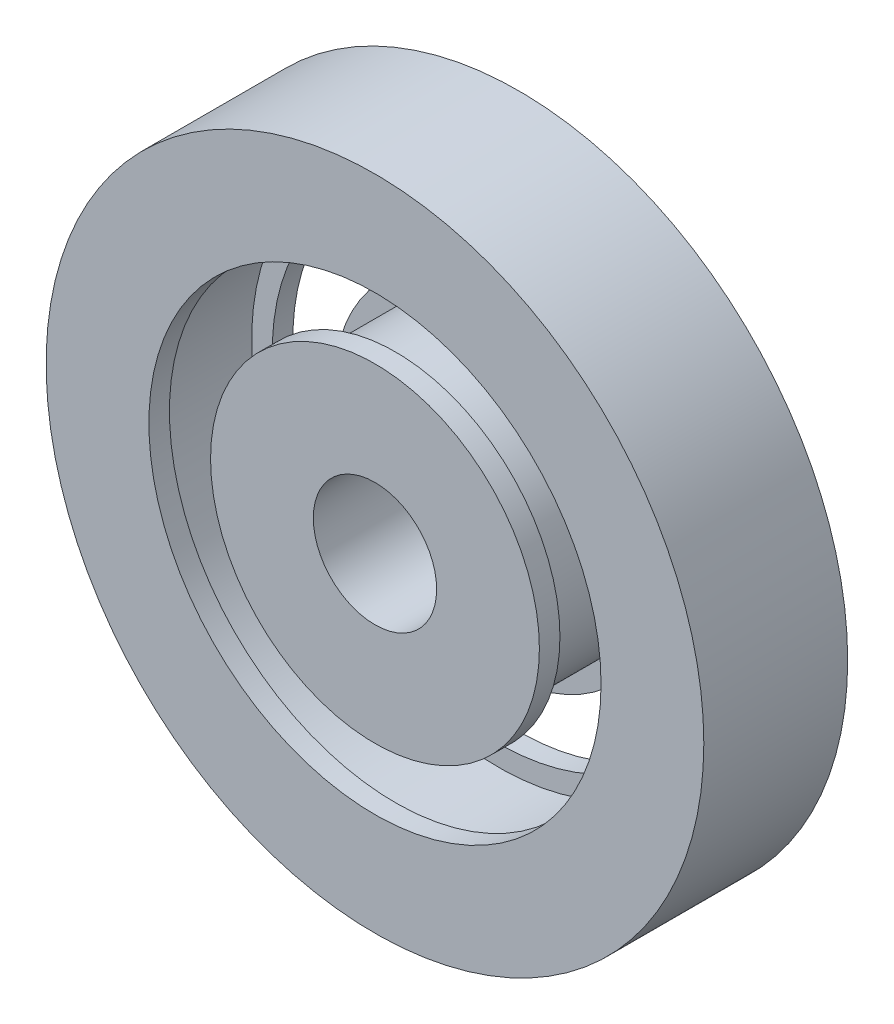
SolidWorks part; units mm, degrees
ref_plane "Front Plane" through (0, 0, 0) normal (0, 0, 1) x (1, 0, 0)
ref_plane "Top Plane" through (0, 0, 0) normal (0, 1, 0) x (1, 0, 0)
ref_plane "Right Plane" through (0, 0, 0) normal (1, 0, 0) x (0, 0, -1)
sketch "Sketch1" plane through (0, 0, 0) normal (0, 0, 1) x (1, 0, 0)
  circle A0 centre (0, 0) radius 32
extrude "Boss-Extrude1" add sketch "Sketch1" along normal blind 14
sketch "Sketch2" plane through (0, 0, 14) normal (0, 0, 1) x (1, 0, 0)
  circle A0 centre (0, 0) radius 24
  circle A1 centre (0, 0) radius 14
  point P4 (0, 0)
extrude "Cut-Extrude1" cut sketch "Sketch2" against normal blind 12
sketch "Sketch3" plane through (0, 0, 14) normal (0, 0, 1) x (1, 0, 0)
  circle A0 centre (0, 0) radius 16
  circle A1 centre (0, 0) radius 14 construction
  circle A2 centre (0, 0) radius 14
extrude "Boss-Extrude2" add sketch "Sketch3" against normal blind 2
sketch "Sketch4" plane through (0, 0, 14) normal (0, 0, 1) x (1, 0, 0)
  circle A0 centre (0, 0) radius 22
  circle A1 centre (0, 0) radius 24 construction
  circle A2 centre (0, 0) radius 24
extrude "Boss-Extrude3" add sketch "Sketch4" against normal blind 2
sketch "Sketch5" plane through (0, 0, 14) normal (0, 0, 1) x (1, 0, 0)
  circle A0 centre (0, 0) radius 22
  circle A1 centre (0, 0) radius 16
extrude "Cut-Extrude2" cut sketch "Sketch5" against normal blind 68
sketch "Sketch6" plane through (0, 0, 0) normal (0, 0, -1) x (-1, 0, 0)
  circle A0 centre (0, 0) radius 6
extrude "Cut-Extrude3" cut sketch "Sketch6" against normal blind 68
